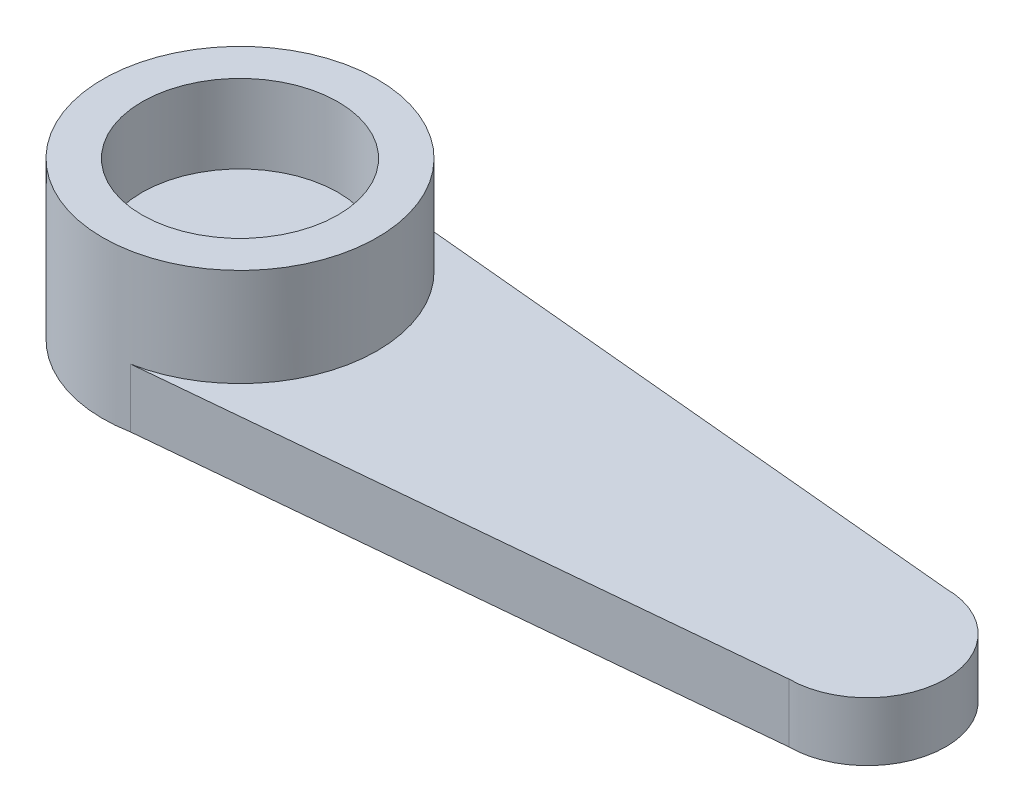
SolidWorks part; units mm, degrees
material "PVC 0.007 Plasticized"
ref_plane "Front Plane" through (0, 0, 0) normal (0, 0, 1) x (1, 0, 0)
ref_plane "Top Plane" through (0, 0, 0) normal (0, 1, 0) x (1, 0, 0)
ref_plane "Right Plane" through (0, 0, 0) normal (1, 0, 0) x (0, 0, -1)
sketch "Sketch1" plane through (0, 0, 0) normal (0, 1, 0) x (1, 0, 0)
  circle A0 centre (0, 0) radius 3.5
  dimension "D1" = 7
extrude "Boss-Extrude1" add sketch "Sketch1" along normal blind 4
sketch "Sketch2" plane through (0, 4, 0) normal (0, 1, 0) x (1, 0, 0)
  circle A0 centre (0, 0) radius 2.5
  dimension "D1" = 5
extrude "Cut-Extrude1" cut sketch "Sketch2" against normal blind 2
sketch "Sketch3" plane through (0, 0, 0) normal (0, 1, 0) x (1, 0, 0)
  line L0 (0, 3.5) -> (16, 2)
  line L1 (0, -3.5) -> (16, -2)
  circle A0 centre (16, 0) radius 2
  circle A1 centre (0, 0) radius 3.5 construction
  circle A2 centre (0, 0) radius 3.5
  dimension "D1" = 4
  dimension "D2" = 16
extrude "Boss-Extrude2" add sketch "Sketch3" along normal blind 1.5 contours A0 | A2 L1 A0 L0
